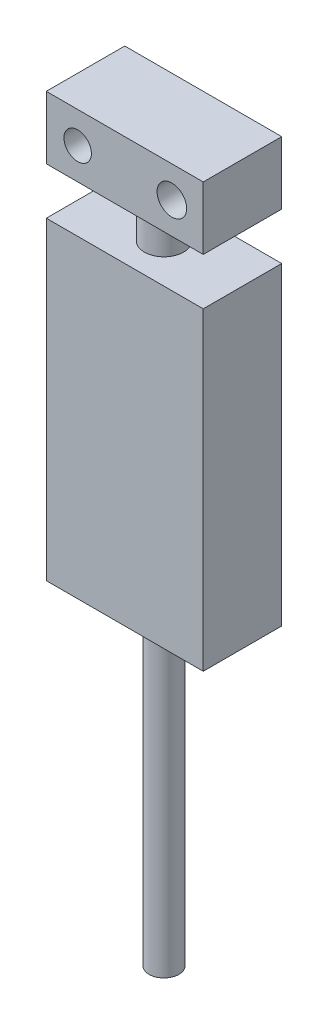
SolidWorks part; units mm, degrees
ref_plane "Front Plane" through (0, 0, 0) normal (0, 0, 1) x (1, 0, 0)
ref_plane "Top Plane" through (0, 0, 0) normal (0, 1, 0) x (1, 0, 0)
ref_plane "Right Plane" through (0, 0, 0) normal (1, 0, 0) x (0, 0, -1)
sketch "Sketch1" plane through (0, 0, 0) normal (0, 0, 1) x (1, 0, 0)
  line L1 (-100, 200) -> (100, 200)
  line L2 (-100, 200) -> (-100, -200)
  line L3 (-100, -200) -> (100, -200)
  line L4 (100, 200) -> (100, -200)
  line L5 (-100, 200) -> (100, -200) construction
  line L6 (-100, -200) -> (100, 200) construction
  point P0 (0, 0)
  dimension "D1" = 400
  dimension "D2" = 200
extrude "Boss-Extrude1" add sketch "Sketch1" along normal blind 100
sketch "Sketch2" plane through (0, 200, 0) normal (0, 1, 0) x (1, 0, 0)
  circle A0 centre (0, -50) radius 25
  dimension "D1" = 50
extrude "Boss-Extrude2" add sketch "Sketch2" along normal blind 60
sketch "Sketch3" plane through (0, 260, 0) normal (0, 1, 0) x (1, 0, 0)
  line L1 (-100, 0) -> (100, 0)
  line L2 (-100, 0) -> (-100, -100)
  line L3 (-100, -100) -> (100, -100)
  line L4 (100, 0) -> (100, -100)
extrude "Boss-Extrude3" add sketch "Sketch3" along normal blind 80
sketch "Sketch4" plane through (0, 0, 100) normal (0, 0, 1) x (1, 0, 0)
  line L0 (-100, 340) -> (100, 340) construction
  line L1 (-100, 340) -> (-100, 260) construction
  circle A0 centre (-60, 300) radius 17.5
  circle A1 centre (60, 300) radius 18.8267
  point P4 (0, 0)
  dimension "D2" = 35
  dimension "D3" = 40
  dimension "D4" = 120
  dimension "D1" = 40
extrude "Cut-Extrude1" cut sketch "Sketch4" against normal blind 40
sketch "Sketch5" plane through (0, -200, 0) normal (0, -1, 0) x (1, 0, 0)
  line L0 (-100, 100) -> (100, 100) construction
  line L1 (100, 100) -> (100, 0) construction
  circle A0 centre (0, 50) radius 19
  point P2 (0, 0)
  dimension "D1" = 50
  dimension "D3" = 38
  dimension "D2" = 100
extrude "Boss-Extrude4" add sketch "Sketch5" along normal blind 400
sketch "Sketch7" plane through (0, 0, 0) normal (0, 0, -1) x (-1, 0, 0)
  line L0 (100, 200) -> (100, -200) construction
  line L1 (-100, 200) -> (100, 200) construction
  circle A0 centre (0, 175) radius 10
  circle A1 centre (-20, -65) radius 10
  circle A2 centre (40, -65) radius 10
  point P10 (0, 0)
  point P11 (0, 0)
  point P13 (100, 12.3291)
  dimension "D1" = 100
  dimension "D6" = 20
  dimension "D2" = 25
  dimension "D3" = 120
  dimension "D4" = 240
  dimension "D5" = 60
extrude "Boss-Extrude5" add sketch "Sketch7" along normal blind 15
